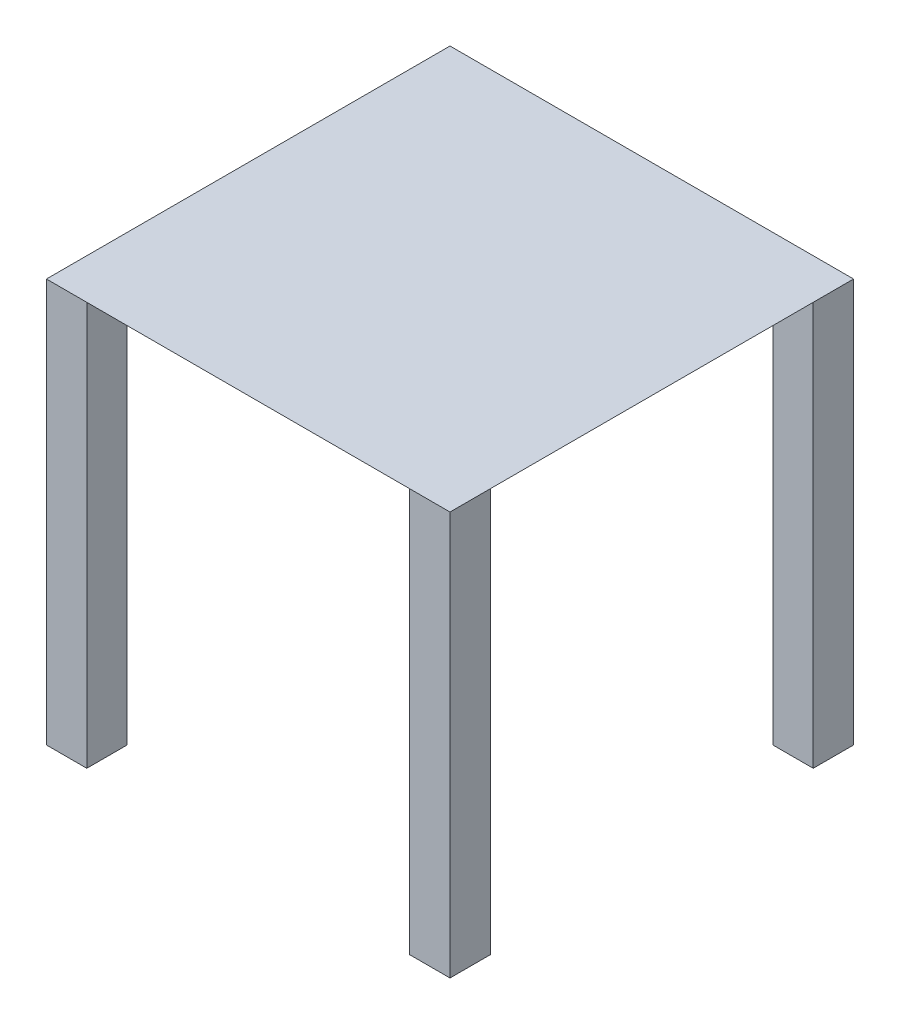
SolidWorks part; units mm, degrees
ref_plane "Front Plane" through (0, 0, 0) normal (0, 0, 1) x (1, 0, 0)
ref_plane "Top Plane" through (0, 0, 0) normal (0, 1, 0) x (1, 0, 0)
ref_plane "Right Plane" through (0, 0, 0) normal (1, 0, 0) x (0, 0, -1)
sketch "Sketch1" plane through (0, 0, 0) normal (0, 1, 0) x (1, 0, 0)
  line L1 (-500, -500) -> (500, -500)
  line L2 (-500, -500) -> (-500, 500)
  line L3 (-500, 500) -> (500, 500)
  line L4 (500, -500) -> (500, 500)
  line L5 (-500, -500) -> (500, 500) construction
  line L6 (-500, 500) -> (500, -500) construction
  point P0 (0, 0)
  dimension "D1" = 1000
  dimension "D2" = 1000
ref_plane "Plane1" through (0, -400, 0) normal (0, -1, 0) x (-1, 0, 0)
sketch "Sketch2" plane through (0, -400, 0) normal (0, -1, 0) x (-1, 0, 0)
  point P0 (0, 0)
loft "Loft1" add profiles "Sketch1", "Sketch2"
sketch "Sketch5" plane through (0, -400, 0) normal (0, -1, 0) x (-1, 0, 0)
  line L0 (500, 500) -> (0, 0) construction
  line L1 (-75, -75) -> (75, -75)
  line L2 (-75, -75) -> (-75, 75)
  line L3 (-75, 75) -> (75, 75)
  line L4 (75, -75) -> (75, 75)
  line L5 (-75, -75) -> (75, 75) construction
  line L6 (-75, 75) -> (75, -75) construction
  point P0 (0, 0)
  dimension "D1" = 150
  dimension "D2" = 150
extrude "Cut-Extrude1" cut sketch "Sketch5" against normal blind 100
sketch "Sketch6" plane through (0, 0, 0) normal (0, 1, 0) x (1, 0, 0)
  line L1 (-500, 500) -> (-400, 500)
  line L2 (-500, 500) -> (-500, 400)
  line L3 (-500, 400) -> (-400, 400)
  line L4 (-400, 500) -> (-400, 400)
  line L5 (500, 500) -> (400, 500)
  line L6 (500, 500) -> (500, 400)
  line L7 (500, 400) -> (400, 400)
  line L8 (400, 500) -> (400, 400)
  line L9 (-500, -500) -> (-400, -500)
  line L10 (-500, -500) -> (-500, -400)
  line L11 (-500, -400) -> (-400, -400)
  line L12 (-400, -500) -> (-400, -400)
  line L13 (500, -500) -> (400, -500)
  line L14 (500, -500) -> (500, -400)
  line L15 (500, -400) -> (400, -400)
  line L16 (400, -500) -> (400, -400)
  dimension "D1" = 100
  dimension "D2" = 100
  dimension "D3" = 100
  dimension "D4" = 100
  dimension "D5" = 100
  dimension "D6" = 100
  dimension "D7" = 100
  dimension "D8" = 100
extrude "Boss-Extrude1" add sketch "Sketch6" against normal blind 1000
